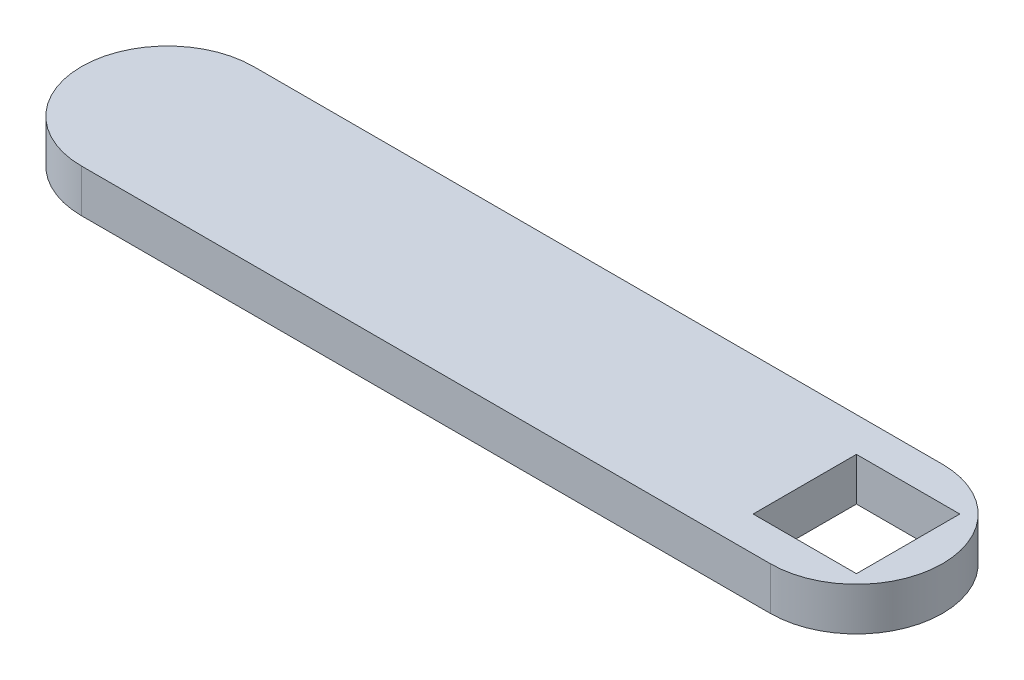
SolidWorks part; units mm, degrees
ref_plane "前视基准面" through (0, 0, 0) normal (0, 0, 1) x (1, 0, 0)
ref_plane "上视基准面" through (0, 0, 0) normal (0, 1, 0) x (1, 0, 0)
ref_plane "右视基准面" through (0, 0, 0) normal (1, 0, 0) x (0, 0, -1)
other "Configuration Table"
sketch "草图1" plane through (0, 0, 0) normal (0, 1, 0) x (1, 0, 0)
  line L0 (-200, 0) -> (200, 0) construction
  line L1 (-200, 50) -> (200, 50)
  line L2 (-200, -50) -> (200, -50)
  arc A0 (-200, 50) -> (-200, -50) centre (-200, 0) ccw
  arc A1 (200, -50) -> (200, 50) centre (200, 0) ccw
  point P2 (0, 0)
  dimension "D1" = 400
  dimension "D2" = 50
extrude "凸台-拉伸1" add sketch "草图1" along normal blind 25
sketch "草图3" plane through (0, 0, 0) normal (0, -1, 0) x (1, 0, 0)
  line L1 (170, 30) -> (230, 30)
  line L2 (170, 30) -> (170, -30)
  line L3 (170, -30) -> (230, -30)
  line L4 (230, 30) -> (230, -30)
  line L5 (170, 30) -> (230, -30) construction
  line L6 (170, -30) -> (230, 30) construction
  point P0 (200, 0)
  dimension "D1" = 60
  dimension "D2" = 60
extrude "切除-拉伸1" cut sketch "草图3" against normal blind 25
